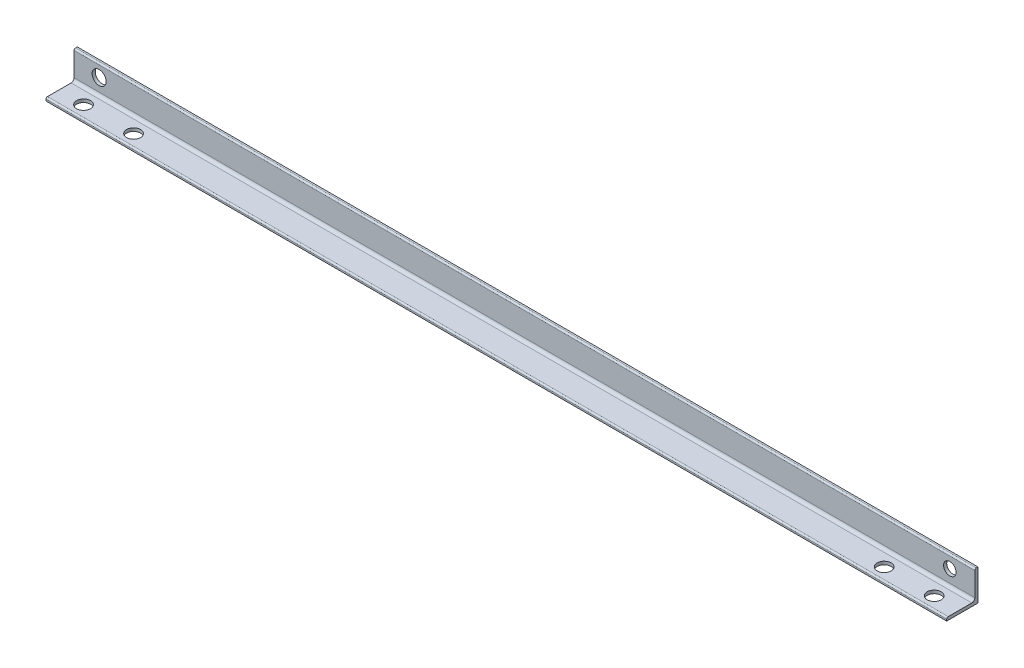
SolidWorks part; units mm, degrees
ref_plane "Front Plane" through (0, 0, 0) normal (0, 0, 1) x (1, 0, 0)
ref_plane "Top Plane" through (0, 0, 0) normal (0, 1, 0) x (1, 0, 0)
ref_plane "Right Plane" through (0, 0, 0) normal (1, 0, 0) x (0, 0, -1)
sketch "Sketch1" plane through (0, 0, 0) normal (1, 0, 0) x (0, 0, -1)
  line L0 (-50.9173, 3.1407) -> (-50.9173, -12.7343)
  line L1 (-50.9173, -12.7343) -> (-66.7923, -12.7343)
  line L2 (-50.9173, 3.1407) -> (-52.5175, 3.1407)
  line L3 (-52.5175, 3.1407) -> (-52.5175, -11.1341)
  line L4 (-52.5175, -11.1341) -> (-66.7923, -11.1341)
  line L5 (-66.7923, -12.7343) -> (-66.7923, -11.1341)
  dimension "D1" = 15.875
  dimension "D2" = 15.875
  dimension "D3" = 1.6002
  dimension "D4" = 1.6002
extrude "Boss-Extrude1" add sketch "Sketch1" along normal blind 457.2
fillet "Fillet1" radius 0.762 2 edges at (228.6, -11.1341, 66.7923) (228.6, 3.1407, 52.5175)
fillet "Fillet2" radius 1.524 1 edges at (228.6, -11.1341, 52.5175)
sketch "Sketch2" plane through (0, -11.1341, 0) normal (0, 1, 0) x (1, 0, 0)
  line L0 (457.2, -54.0415) -> (457.2, -66.0303) construction
  line L1 (457.2, -66.7923) -> (0, -66.7923) construction
  line L2 (0, -54.0415) -> (0, -66.0303) construction
  circle A0 centre (444.5, -60.4423) radius 3.556
  circle A1 centre (419.1, -60.4423) radius 3.556
  circle A2 centre (12.7, -60.4423) radius 3.556
  circle A3 centre (38.1, -60.4423) radius 3.556
  dimension "D1" = 7.112
  dimension "D2" = 7.112
  dimension "D3" = 12.7
  dimension "D4" = 38.1
  dimension "D5" = 6.35
  dimension "D6" = 6.35
  dimension "D7" = 7.112
  dimension "D8" = 7.112
  dimension "D9" = 38.1
  dimension "D10" = 12.7
  dimension "D11" = 6.35
  dimension "D12" = 6.35
extrude "Cut-Extrude1" cut sketch "Sketch2" against normal through all
sketch "Sketch3" plane through (0, 0, 52.5175) normal (0, 0, 1) x (1, 0, 0)
  line L0 (0, 3.1407) -> (457.2, 3.1407) construction
  line L1 (0, 2.3787) -> (0, -9.6101) construction
  line L2 (457.2, 2.3787) -> (457.2, -9.6101) construction
  circle A0 centre (12.7, -3.2093) radius 3.556
  circle A1 centre (444.5, -3.2093) radius 3.175
  dimension "D1" = 7.112
  dimension "D2" = 6.35
  dimension "D3" = 12.7
  dimension "D4" = 6.35
  dimension "D5" = 6.35
  dimension "D6" = 12.7
extrude "Cut-Extrude2" cut sketch "Sketch3" against normal through all
